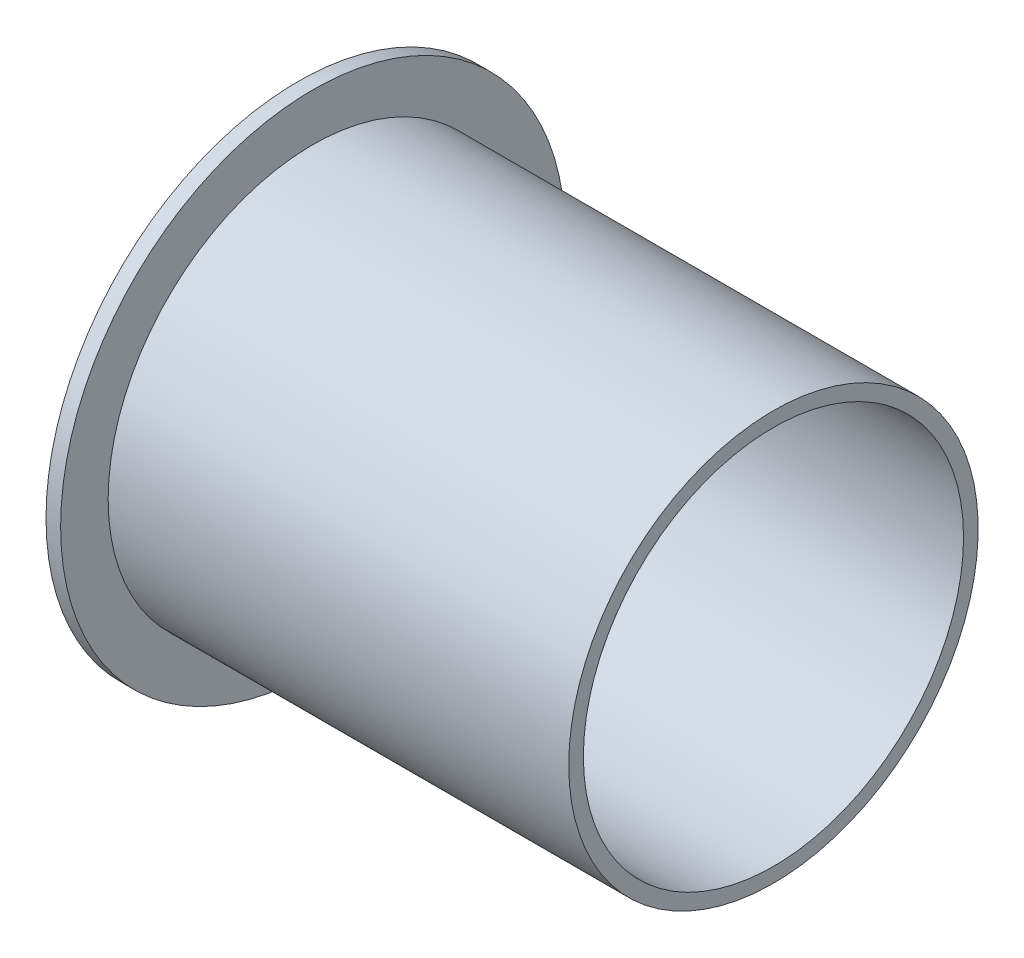
SolidWorks part; units mm, degrees
material "Brass"
ref_plane "Front Plane" through (0, 0, 0) normal (0, 0, 1) x (1, 0, 0)
ref_plane "Top Plane" through (0, 0, 0) normal (0, 1, 0) x (1, 0, 0)
ref_plane "Right Plane" through (0, 0, 0) normal (1, 0, 0) x (0, 0, -1)
sketch "Sketch1" plane through (0, 0, 0) normal (0, 1, 0) x (1, 0, 0)
  line L0 (-54.3054, 0) -> (78.6234, 0) construction
  line L1 (0, 34.5) -> (0, 26)
  line L2 (0, 26) -> (65, 26)
  line L3 (65, 26) -> (65, 28)
  line L4 (65, 28) -> (2, 28)
  line L5 (2, 28) -> (2, 34.5)
  line L6 (2, 34.5) -> (0, 34.5)
  dimension "D1" = 2
  dimension "D2" = 2
  dimension "D3" = 65
  dimension "D4" = 34.5
  dimension "D5" = 56
revolve "Revolve1" add sketch "Sketch1" angle 360 about L0
